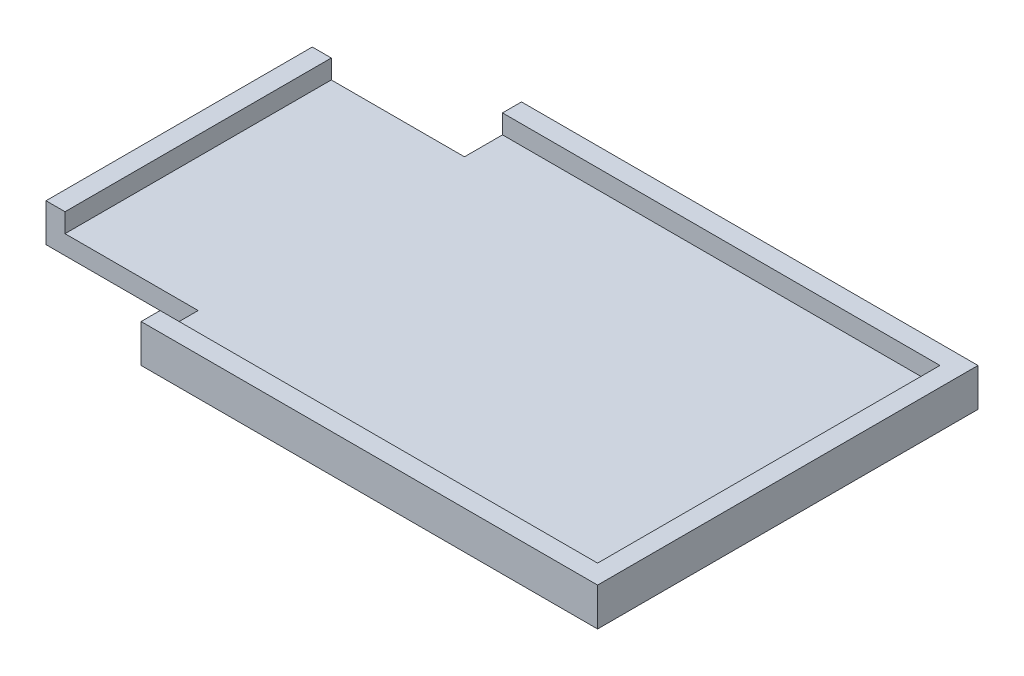
SolidWorks part; units mm, degrees
ref_plane "Front Plane" through (0, 0, 0) normal (0, 0, 1) x (1, 0, 0)
ref_plane "Top Plane" through (0, 0, 0) normal (0, 1, 0) x (1, 0, 0)
ref_plane "Right Plane" through (0, 0, 0) normal (1, 0, 0) x (0, 0, -1)
sketch "Sketch1" plane through (0, 0, 0) normal (0, 1, 0) x (1, 0, 0)
  line L0 (-101.6, 44.45) -> (-50.8, 44.45)
  line L1 (-50.8, 63.5) -> (101.6, 63.5)
  line L2 (-101.6, 44.45) -> (-101.6, -44.45)
  line L3 (-50.8, -63.5) -> (101.6, -63.5)
  line L4 (101.6, 63.5) -> (101.6, -63.5)
  line L9 (-50.8, 44.45) -> (-50.8, 63.5)
  line L10 (-101.6, -44.45) -> (-50.8, -44.45)
  line L11 (-50.8, -44.45) -> (-50.8, -63.5)
  point P6 (101.6, 0)
  dimension "D2" = 127
  dimension "D3" = 203.2
  dimension "D6" = 19.05
  dimension "D7" = 50.8
extrude "Boss-Extrude1" add sketch "Sketch1" along normal blind 12.7
sketch "Sketch2" plane through (0, 12.7, 0) normal (0, 1, 0) x (1, 0, 0)
  line L0 (101.6, 63.5) -> (-50.8, 63.5) construction
  line L1 (-95.25, 57.15) -> (95.25, 57.15)
  line L2 (-95.25, 57.15) -> (-95.25, -57.15)
  line L3 (-95.25, -57.15) -> (95.25, -57.15)
  line L4 (95.25, 57.15) -> (95.25, -57.15)
  line L5 (101.6, -63.5) -> (101.6, 63.5) construction
  point P8 (0, 57.15)
  point P11 (95.25, 0)
  dimension "D1" = 6.35
  dimension "D2" = 6.35
extrude "Cut-Extrude1" cut sketch "Sketch2" against normal blind 6.35
